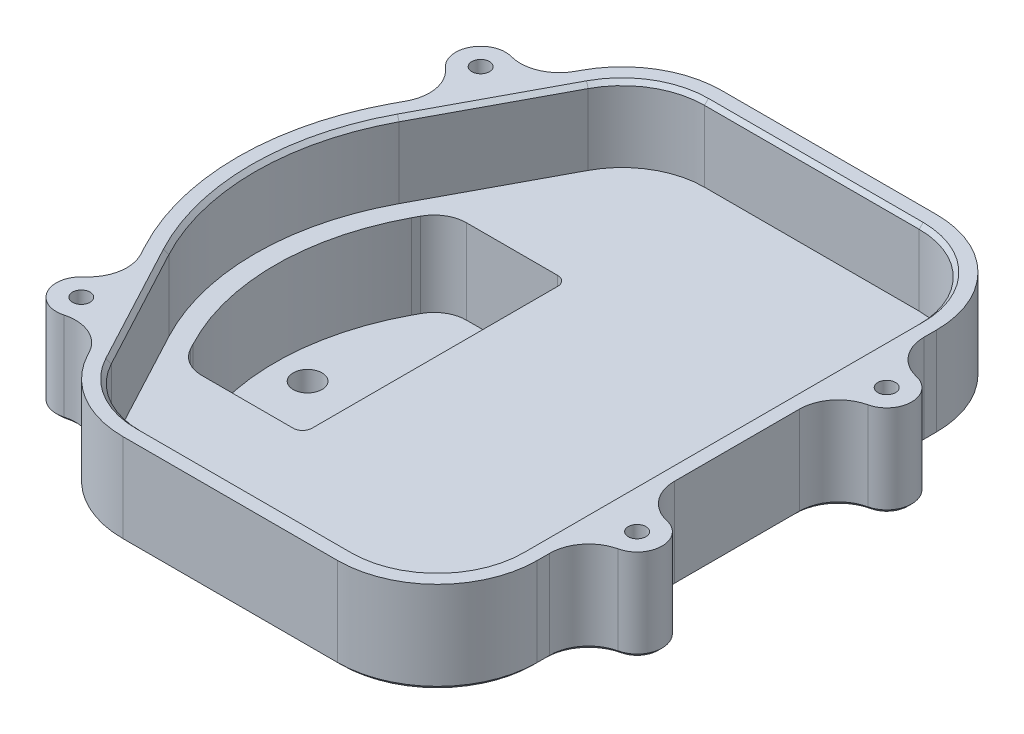
SolidWorks part; units mm, degrees
material "6061-T6 (SS)"
ref_plane "Front Plane" through (0, 0, 0) normal (0, 0, 1) x (1, 0, 0)
ref_plane "Top Plane" through (0, 0, 0) normal (0, 1, 0) x (1, 0, 0)
ref_plane "Right Plane" through (0, 0, 0) normal (1, 0, 0) x (0, 0, -1)
sketch "Sketch1" plane through (0, 0, 0) normal (0, 1, 0) x (1, 0, 0)
  line L0 (-57.15, 0) -> (-57.15, -50000) construction
  line L1 (-25.4, -76.2) -> (-25.4, -101.6) construction
  line L2 (-25.4, -76.2) -> (69.85, -76.2)
  line L3 (-25.4, 76.2) -> (69.85, 76.2)
  line L4 (69.85, -76.2) -> (69.85, 76.2)
  line L5 (-25.4, 76.2) -> (-25.4, 101.6) construction
  line L6 (0, 0) -> (0, -50000) construction
  line L7 (-49.3059, 31.3765) -> (-25.4, 76.2)
  line L8 (-57.15, 0) -> (69.85, 0) construction
  line L9 (-49.3059, -31.3765) -> (-25.4, -76.2)
  arc A0 (-49.3059, -31.3765) -> (-49.3059, 31.3765) centre (9.525, 0) cw
  point P0 (0, 0)
  dimension "D5" = 50.8
  dimension "D1" = 76.2
  dimension "D2" = 25.4
  dimension "D3" = 25.4
  dimension "D4" = 69.85
  dimension "D6" = 127
extrude "Boss-Extrude1" add sketch "Sketch1" along normal blind 23.495
fillet "Fillet1" radius 25.4 4 edges at (-25.4, 11.7475, 76.2) (69.85, 11.7475, 76.2) (69.85, 11.7475, -76.2) (-25.4, 11.7475, -76.2)
shell "Shell1" thickness 4.445
sketch "Sketch13" plane through (0, 0, 0) normal (0, -1, 0) x (1, 0, 0)
  line L0 (0, 0) -> (-50000, 0) construction
  line L1 (-2.54, 38.1) -> (-2.54, -38.1)
  line L2 (-2.54, 38.1) -> (-40.2167, 38.1)
  line L3 (-49.3059, 31.3765) -> (-32.5718, 62.7529) construction
  line L4 (-40.2167, -38.1) -> (-2.54, -38.1)
  line L12 (-40.2167, -38.1) -> (-44.5994, -29.8824)
  line L13 (-44.5994, 29.8824) -> (-40.2167, 38.1)
  arc A1 (-49.3059, 31.3765) -> (-49.3059, -31.3765) centre (9.525, 0) ccw construction
  arc A5 (-44.5994, 29.8824) -> (-44.5994, -29.8824) centre (11.43, 0) ccw
  dimension "D3" = 49.53
  dimension "D2" = 63.5
  dimension "D5" = 54.61
  dimension "D1" = 76.2
extrude "nub" add sketch "Sketch13" along normal blind 23.368
fillet "Fillet2" radius 12.7 2 edges at (-40.2167, -11.684, -38.1) (-40.2167, -11.684, 38.1)
fillet "Fillet3" radius 6.858 2 edges at (-2.54, -11.684, -38.1) (-2.54, -11.684, 38.1)
sketch "Sketch8" plane through (0, 4.445, 0) normal (0, 1, 0) x (1, 0, 0)
  line L24 (-6.985, -31.242) -> (-6.985, 31.242)
  line L25 (-32.5967, -33.655) -> (-9.398, -33.655)
  line L26 (-40.6774, -27.7906) -> (-39.8805, -29.2847)
  line L27 (-39.8805, 29.2847) -> (-40.6774, 27.7906)
  line L28 (-32.5967, -33.655) -> (-9.398, -33.655)
  line L29 (-6.985, -31.242) -> (-6.985, 31.242)
  line L30 (-9.398, 33.655) -> (-32.5967, 33.655)
  line L31 (-40.6774, -27.7906) -> (-39.8805, -29.2847)
  line L32 (-39.8805, 29.2847) -> (-40.6774, 27.7906)
  line L33 (-9.398, 33.655) -> (-32.5967, 33.655)
  arc A30 (-6.985, 31.242) -> (-9.398, 33.655) centre (-9.398, 31.242) ccw
  arc A31 (-6.985, 31.242) -> (-9.398, 33.655) centre (-9.398, 31.242) ccw
  arc A32 (-40.6774, 27.7906) -> (-40.6774, -27.7906) centre (11.43, 0) ccw
  arc A33 (-39.8805, -29.2847) -> (-32.5967, -33.655) centre (-32.5967, -25.4) ccw
  arc A34 (-39.8805, -29.2847) -> (-32.5967, -33.655) centre (-32.5967, -25.4) ccw
  arc A35 (-32.5967, 33.655) -> (-39.8805, 29.2847) centre (-32.5967, 25.4) ccw
  arc A36 (-32.5967, 33.655) -> (-39.8805, 29.2847) centre (-32.5967, 25.4) ccw
  arc A37 (-40.6774, 27.7906) -> (-40.6774, -27.7906) centre (11.43, 0) ccw
  arc A38 (-9.398, -33.655) -> (-6.985, -31.242) centre (-9.398, -31.242) ccw
  arc A39 (-9.398, -33.655) -> (-6.985, -31.242) centre (-9.398, -31.242) ccw
  dimension "D1" = 4.445
extrude "Cut-Extrude1" cut sketch "Sketch8" against normal offset from surface (21.463 mm away) 6.35 up to face at (-27.2365, -23.368, 0)
chamfer "Chamfer1" distance 1.016 angle 45 10 edges at (-37.0168, 23.495, 44.9729) (-20.9413, 23.495, 68.7688) (-52.705, 23.495, 0) (17.145, 23.495, 71.755) (-37.0168, 23.495, -44.9729) (59.2674, 23.495, 65.6174) (-20.9413, 23.495, -68.7688) (65.405, 23.495, 0) (17.145, 23.495, -71.755) (59.2674, 23.495, -65.6174)
sketch "Sketch10" plane through (0, 23.495, 0) normal (0, 1, 0) x (1, 0, 0)
  line L0 (69.85, 47.625) -> (69.85, 15.875)
  line L1 (69.85, -50.8) -> (69.85, 50.8) construction
  line L2 (0, 0) -> (50000, 0) construction
  line L3 (69.85, -47.625) -> (69.85, -15.875)
  line L4 (-33.0698, 61.8191) -> (-48.011, 33.8044)
  line L5 (-32.5718, 62.7529) -> (-49.3059, 31.3765) construction
  line L6 (-44.4579, 56.9222) -> (-50.2886, 45.9897) construction
  line L7 (-42.0859, 47.888) -> (40559.6261, -29092.0967) construction
  line L8 (-44.4579, -56.9222) -> (-50.2886, -45.9897) construction
  line L9 (-33.0698, -61.8191) -> (-48.011, -33.8044)
  arc A0 (69.85, 47.625) -> (77.5939, 37.9451) centre (79.7719, 47.625) ccw
  arc A1 (77.5939, 37.9451) -> (77.5939, 25.5549) centre (76.2, 31.75) cw
  arc A2 (77.5939, -25.5549) -> (69.85, -15.875) centre (79.7719, -15.875) cw
  arc A3 (77.5939, 25.5549) -> (69.85, 15.875) centre (79.7719, 15.875) ccw
  arc A4 (77.5939, -37.9451) -> (77.5939, -25.5549) centre (76.2, -31.75) ccw
  arc A5 (69.85, -47.625) -> (77.5939, -37.9451) centre (79.7719, -47.625) cw
  arc A6 (-33.0698, 61.8191) -> (-44.4579, 56.9222) centre (-41.8244, 66.4882) cw
  arc A7 (-44.4579, 56.9222) -> (-50.2886, 45.9897) centre (-46.1433, 50.8) ccw
  arc A8 (-50.2886, 45.9897) -> (-48.011, 33.8044) centre (-56.7656, 38.4735) cw
  arc A9 (-50.2886, -45.9897) -> (-48.011, -33.8044) centre (-56.7656, -38.4735) ccw
  arc A10 (-44.4579, -56.9222) -> (-50.2886, -45.9897) centre (-46.1433, -50.8) cw
  arc A11 (-33.0698, -61.8191) -> (-44.4579, -56.9222) centre (-41.8244, -66.4882) ccw
  point P30 (-40.9388, 47.0647)
  dimension "D1" = 6.35
  dimension "D6" = 6.35
  dimension "D2" = 31.75
  dimension "D3" = 6.35
  dimension "D4" = 31.75
  dimension "D5" = 31.75
  dimension "D7" = 6.35
  dimension "D8" = 50.8
extrude "Boss-Extrude2" add sketch "Sketch10" against normal up to surface (23.495 mm away) up to face at (4.3477, 0, 0)
hole_wizard "#8 Clearance Hole1" positions "Sketch12" profile "Sketch11" hole size "#8" standard "Ansi Inch" end condition through all
sketch "Sketch12" plane through (0, 23.495, 0) normal (0, 1, 0) x (-1, 0, 0)
  arc A0 (44.4579, -56.9222) -> (50.2886, -45.9897) centre (46.1433, -50.8) ccw construction
  arc A1 (50.2886, 45.9897) -> (44.4579, 56.9222) centre (46.1433, 50.8) ccw construction
  arc A2 (-77.5939, 37.9451) -> (-77.5939, 25.5549) centre (-76.2, 31.75) ccw construction
  arc A3 (-77.5939, -25.5549) -> (-77.5939, -37.9451) centre (-76.2, -31.75) ccw construction
  point P0 (46.1433, -50.8)
  point P1 (46.1433, 50.8)
  point P3 (-76.2, 31.75)
  point P5 (-76.2, -31.75)
sketch "Sketch11" plane through (-46.1433, 23.495, -50.8) normal (1, 0, 0) x (0, 0, 1)
  line L0 (0, 0) -> (0, 46.863)
  line L1 (0, 46.863) -> (2.2479, 46.863)
  line L2 (2.2479, 46.863) -> (2.2479, 0)
  line L5 (2.2479, 0) -> (0, 0)
  line L11 (0, -6.35) -> (0, 107.95) construction
  dimension "Thru Hole Dia." = 4.4958
  dimension "Thru Hole Depth" = 46.863
chamfer "Chamfer2" distance 1.016 angle 45 36 edges at (-32.8208, 0, 62.286) (-23.2282, 0, 72.5803) (17.145, 0, 76.2) (62.4105, 0, 68.7605) (69.85, 0, 49.2125) (-57.15, 0, 0) (69.85, 0, -49.2125) (-32.8208, 0, -62.286) (62.4105, 0, -68.7605) (-23.2282, 0, -72.5803) (17.145, 0, -76.2) (-37.905, 0, 57.3733) (-51.7463, 0, 53.7882) (72.0242, 0, 41.4269) (-47.0126, 0, 40.2965) (82.55, 0, 31.75) (-48.6584, 0, 32.5904) (72.0242, 0, 22.0731) (69.85, 0, 0) (-48.6584, 0, -32.5904) (72.0242, 0, -22.0731) (-47.0126, 0, -40.2965) (82.55, 0, -31.75) (-51.7463, 0, -53.7882) (72.0242, 0, -41.4269) (-37.905, 0, -57.3733) (-2.54, -23.368, 0) (-20.9973, -23.368, 38.1) (-20.9973, -23.368, -38.1) (-39.1308, -23.368, 36.2902) (-39.1308, -23.368, -36.2902) (-44.201, -23.368, 30.6294) (-44.201, -23.368, -30.6294) (-52.07, -23.368, 0) (-4.5487, -23.368, 36.0913) (-4.5487, -23.368, -36.0913)
sketch "Sketch14" plane through (0, -23.368, 0) normal (0, -1, 0) x (1, 0, 0)
  line L0 (0, 0) -> (50000, 0) construction
  line L1 (-2.54, -31.242) -> (-2.54, 31.242) construction
  circle A0 centre (-16.51, 22.86) radius 3.675
  circle A1 centre (-16.51, 0) radius 3.675
  circle A2 centre (-16.51, -22.86) radius 3.675
  circle A3 centre (-39.37, 0) radius 3.675
  dimension "D1" = 7.35
  dimension "D2" = 45.72
  dimension "D3" = 22.86
  dimension "D4" = 13.97
extrude "Cut-Extrude2" cut sketch "Sketch14" against normal through all
